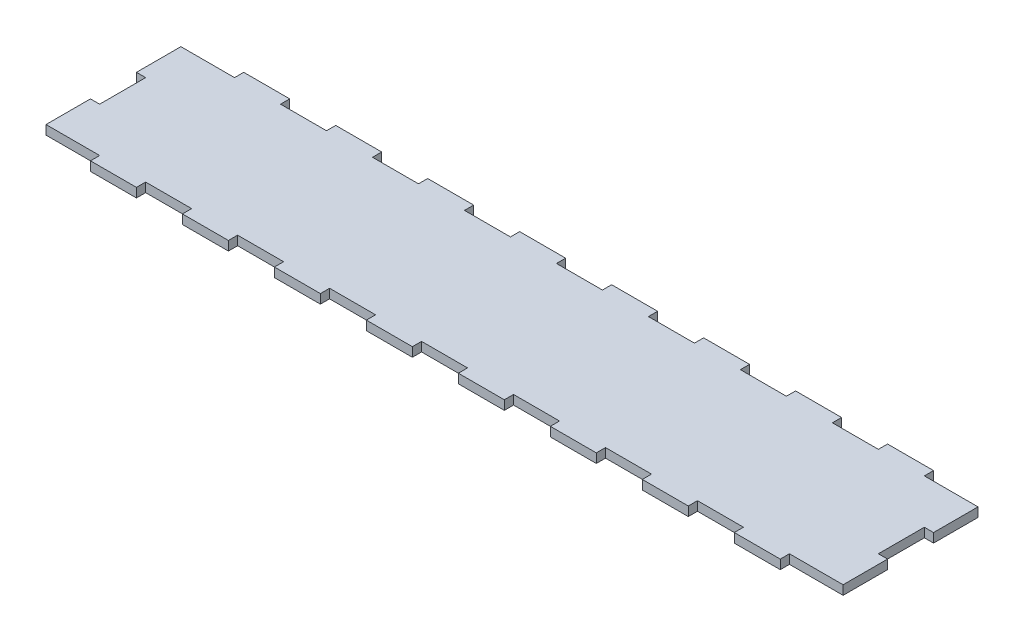
SolidWorks part; units mm, degrees
ref_plane "Alzado" through (0, 0, 0) normal (0, 0, 1) x (1, 0, 0)
ref_plane "Planta" through (0, 0, 0) normal (0, 1, 0) x (1, 0, 0)
ref_plane "Vista lateral" through (0, 0, 0) normal (1, 0, 0) x (0, 0, -1)
sketch "Croquis1" plane through (0, 0, 0) normal (0, 1, 0) x (1, 0, 0)
  line L0 (17.5, 0) -> (32.5, 0)
  line L1 (260, 3) -> (260, 17.5)
  line L2 (242.5, 50) -> (227.5, 50)
  line L3 (0, 47) -> (0, 32.5)
  line L5 (212.5, 50) -> (197.5, 50)
  line L6 (3, 17.5) -> (3, 32.5)
  line L7 (3, 32.5) -> (0, 32.5)
  line L8 (137.5, 47) -> (122.5, 47)
  line L9 (122.5, 47) -> (122.5, 50)
  line L10 (122.5, 50) -> (107.5, 50)
  line L11 (107.5, 50) -> (107.5, 47)
  line L12 (107.5, 47) -> (92.5, 47)
  line L13 (92.5, 47) -> (92.5, 50)
  line L14 (92.5, 50) -> (77.5, 50)
  line L15 (77.5, 50) -> (77.5, 47)
  line L16 (77.5, 47) -> (62.5, 47)
  line L17 (62.5, 47) -> (62.5, 50)
  line L18 (62.5, 50) -> (47.5, 50)
  line L19 (47.5, 50) -> (47.5, 47)
  line L20 (47.5, 47) -> (32.5, 47)
  line L21 (32.5, 47) -> (32.5, 50)
  line L22 (32.5, 50) -> (17.5, 50)
  line L23 (17.5, 50) -> (17.5, 47)
  line L24 (17.5, 47) -> (0, 47)
  line L25 (242.5, 47) -> (260, 47)
  line L26 (242.5, 50) -> (242.5, 47)
  line L27 (227.5, 47) -> (227.5, 50)
  line L28 (212.5, 47) -> (227.5, 47)
  line L29 (212.5, 50) -> (212.5, 47)
  line L30 (197.5, 47) -> (197.5, 50)
  line L31 (182.5, 47) -> (197.5, 47)
  line L32 (182.5, 50) -> (182.5, 47)
  line L33 (167.5, 47) -> (167.5, 50)
  line L34 (152.5, 47) -> (167.5, 47)
  line L35 (152.5, 50) -> (152.5, 47)
  line L36 (137.5, 47) -> (137.5, 50)
  line L37 (257, 32.5) -> (260, 32.5)
  line L38 (257, 17.5) -> (257, 32.5)
  line L40 (257, 17.5) -> (260, 17.5)
  line L41 (137.5, 3) -> (137.5, 0)
  line L42 (152.5, 0) -> (152.5, 3)
  line L43 (152.5, 3) -> (167.5, 3)
  line L44 (167.5, 3) -> (167.5, 0)
  line L45 (182.5, 0) -> (182.5, 3)
  line L46 (182.5, 3) -> (197.5, 3)
  line L47 (197.5, 3) -> (197.5, 0)
  line L48 (212.5, 0) -> (212.5, 3)
  line L49 (212.5, 3) -> (227.5, 3)
  line L50 (227.5, 3) -> (227.5, 0)
  line L51 (242.5, 0) -> (242.5, 3)
  line L52 (242.5, 3) -> (260, 3)
  line L53 (17.5, 3) -> (0, 3)
  line L54 (17.5, 0) -> (17.5, 3)
  line L55 (32.5, 3) -> (32.5, 0)
  line L56 (47.5, 3) -> (32.5, 3)
  line L57 (47.5, 0) -> (47.5, 3)
  line L58 (62.5, 3) -> (62.5, 0)
  line L59 (77.5, 3) -> (62.5, 3)
  line L60 (77.5, 0) -> (77.5, 3)
  line L61 (92.5, 3) -> (92.5, 0)
  line L62 (107.5, 3) -> (92.5, 3)
  line L63 (107.5, 0) -> (107.5, 3)
  line L64 (122.5, 3) -> (122.5, 0)
  line L65 (137.5, 3) -> (122.5, 3)
  line L66 (3, 17.5) -> (0, 17.5)
  line L67 (92.5, 50) -> (77.5, 50)
  line L68 (0, 17.5) -> (0, 3)
  line L69 (47.5, 0) -> (62.5, 0)
  line L70 (77.5, 0) -> (92.5, 0)
  line L71 (107.5, 0) -> (122.5, 0)
  line L72 (137.5, 0) -> (152.5, 0)
  line L73 (167.5, 0) -> (182.5, 0)
  line L74 (197.5, 0) -> (212.5, 0)
  line L75 (227.5, 0) -> (242.5, 0)
  line L76 (260, 32.5) -> (260, 47)
  line L77 (182.5, 50) -> (167.5, 50)
  line L78 (152.5, 50) -> (137.5, 50)
  line L79 (122.5, 50) -> (107.5, 50)
  line L80 (62.5, 50) -> (47.5, 50)
  line L81 (32.5, 50) -> (17.5, 50)
  dimension "D7" = 15
  dimension "D8" = 15
  dimension "D9" = 15
  dimension "D10" = 15
  dimension "D11" = 15
  dimension "D12" = 15
  dimension "D13" = 15
extrude "Saliente-Extruir1" add sketch "Croquis1" along normal blind 3 contours L35 L78 L36 L8 L9 L10 L11 L12 L13 L14 L15 L16 L17 L18 L19 L20 L21 L22 L23 L24 L3 L7 L6 L66 L68 L53 L54 L0 L55 L56 L57 L69 L58 L59 L60 L70 L61 L62 L63 L71 L64 L65 L41 L72 L42 L43 L44 L73 L45 L46 L47
